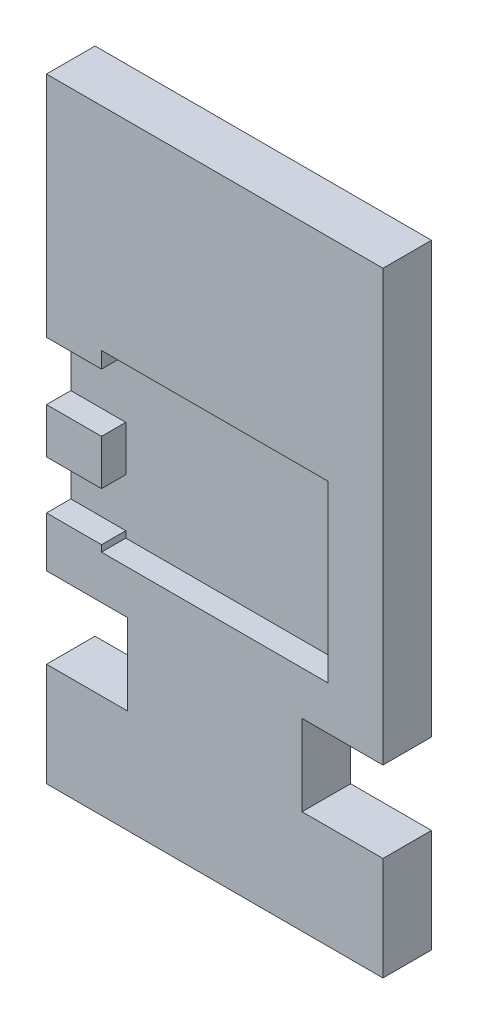
SolidWorks part; units mm, degrees
ref_plane "Front Plane" through (0, 0, 0) normal (0, 0, 1) x (1, 0, 0)
ref_plane "Top Plane" through (0, 0, 0) normal (0, 1, 0) x (1, 0, 0)
ref_plane "Right Plane" through (0, 0, 0) normal (1, 0, 0) x (0, 0, -1)
sketch "Sketch1" plane through (0, 0, 0) normal (0, 0, 1) x (1, 0, 0)
  line L1 (0, 0) -> (52, 0)
  line L2 (0, 0) -> (0, 190)
  line L3 (0, 190) -> (52, 190)
  line L4 (52, 0) -> (52, 190)
  dimension "D1" = 190
  dimension "D2" = 52
extrude "Boss-Extrude1" add sketch "Sketch1" along normal blind 15
sketch "Sketch2" plane through (0, 0, 15) normal (0, 0, 1) x (1, 0, 0)
  line L6 (52, 0) -> (52, 190) construction
  line L11 (52, 124.5) -> (17, 124.5)
  line L12 (52, 124.5) -> (52, 70.5)
  line L13 (52, 70.5) -> (17, 70.5)
  line L14 (17, 124.5) -> (17, 70.5)
  dimension "D6" = 54
  dimension "D7" = 35
extrude "Cut-Extrude1" cut sketch "Sketch2" against normal blind 7.5
ref_plane "Plane1" through (52, 0, 0) normal (1, 0, 0) x (0, 0, -1)
sketch "Sketch4" plane through (0, 0, 0) normal (0, 0, -1) x (-1, 0, 0)
  line L1 (-70, 180) -> (-34, 180)
  line L2 (-70, 180) -> (-70, 133)
  line L3 (-70, 133) -> (-34, 133)
  line L4 (-34, 180) -> (-34, 133)
  line L5 (-52, 190) -> (0, 190) construction
  line L6 (0, 190) -> (0, 0) construction
  point P6 (-52, 180)
  dimension "D1" = 47
  dimension "D2" = 36
  dimension "D3" = 10
  dimension "D4" = 52
extrude "Cut-Extrude7" cut sketch "Sketch4" against normal blind 5
sketch "Sketch9" plane through (0, 0, 15) normal (0, 0, 1) x (1, 0, 0)
  line L0 (0, 190) -> (0, 0) construction
  line L1 (0, 57) -> (25, 57)
  line L2 (0, 57) -> (0, 32)
  line L3 (0, 32) -> (25, 32)
  line L4 (25, 57) -> (25, 32)
  line L5 (0, 0) -> (52, 0) construction
  dimension "D1" = 32
  dimension "D2" = 25
  dimension "D3" = 25
extrude "Cut-Extrude8" cut sketch "Sketch9" against normal through all
sketch "Sketch5" plane through (17, 0, 0) normal (1, 0, 0) x (0, 0, -1)
  line L0 (-15, 124.5) -> (-15, 70.5) construction
  line L1 (-15, 119.5) -> (-7.5, 119.5)
  line L2 (-15, 119.5) -> (-15, 72.5)
  line L3 (-15, 72.5) -> (-7.5, 72.5)
  line L4 (-7.5, 119.5) -> (-7.5, 72.5)
  line L5 (-7.5, 124.5) -> (-7.5, 70.5) construction
  line L6 (-7.5, 70.5) -> (-15, 70.5) construction
  line L7 (-7.5, 124.5) -> (-15, 124.5) construction
  line L9 (-15, 101.5) -> (-7.5, 101.5)
  line L10 (-15, 101.5) -> (-15, 87.5)
  line L11 (-15, 87.5) -> (-7.5, 87.5)
  line L12 (-7.5, 101.5) -> (-7.5, 87.5)
  line M3 (-15, 124.5) -> (-15, 70.5)
  line M5 (-7.5, 70.5) -> (-7.5, 124.5)
  dimension "D1" = 2
  dimension "D2" = 5
  dimension "D3" = 18
  dimension "D4" = 15
extrude "Cut-Extrude5" cut sketch "Sketch5" against normal blind 20 contours L9 L4 L1 M3 | L11 L3 M3 M5
mirror "Mirror4" about plane through (52, 0, 0) normal (1, 0, 0) of "Boss-Extrude1", "Cut-Extrude1", "Cut-Extrude7", "Cut-Extrude8"
